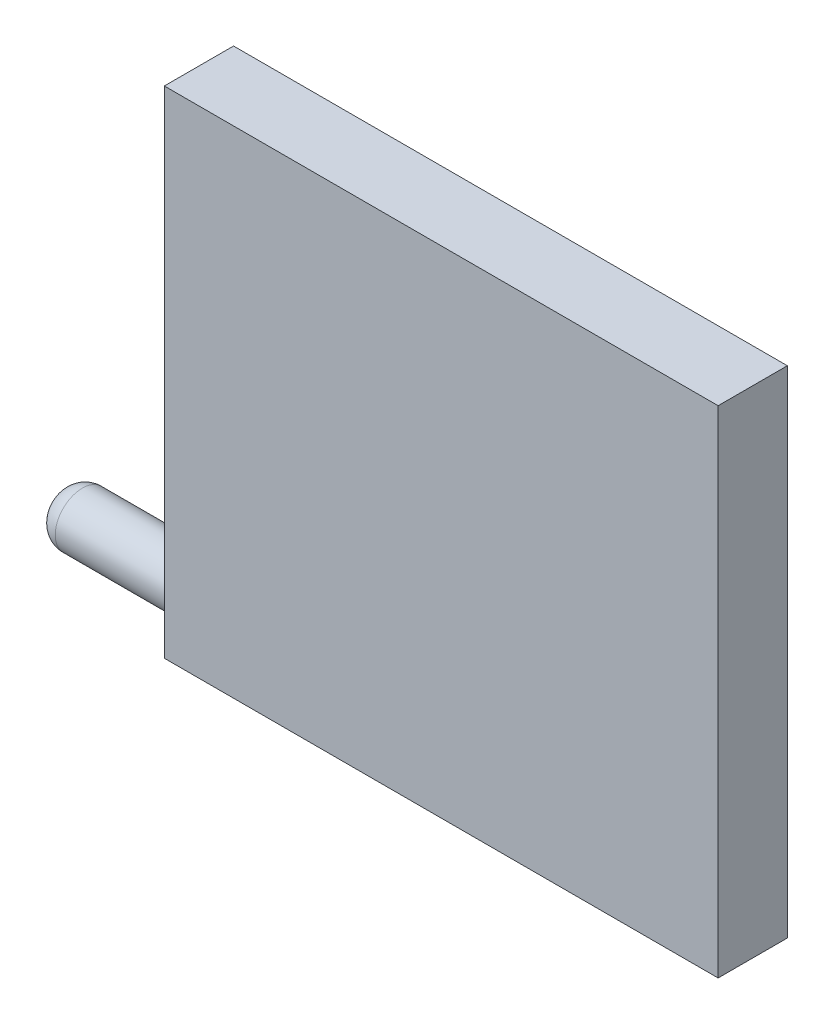
SolidWorks part; units mm, degrees
ref_plane "Front Plane" through (0, 0, 0) normal (0, 0, 1) x (1, 0, 0)
ref_plane "Top Plane" through (0, 0, 0) normal (0, 1, 0) x (1, 0, 0)
ref_plane "Right Plane" through (0, 0, 0) normal (1, 0, 0) x (0, 0, -1)
sketch "Sketch1" plane through (0, 0, 0) normal (0, 0, 1) x (1, 0, 0)
  line L1 (0, 0) -> (80, 0)
  line L2 (0, 0) -> (0, -71.5974)
  line L3 (0, -71.5974) -> (80, -71.5974)
  line L4 (80, 0) -> (80, -71.5974)
  dimension "D1" = 80
extrude "Boss-Extrude1" add sketch "Sketch1" along normal blind 10
sketch "Sketch2" plane through (0, 0, 0) normal (-1, 0, 0) x (0, 0, 1)
  circle A0 centre (4.8492, -65.2995) radius 3.9097
extrude "Boss-Extrude2" add sketch "Sketch2" along normal blind 20
fillet "Fillet1" radius 3 1 edges at (-20, -65.2995, 8.7589)
